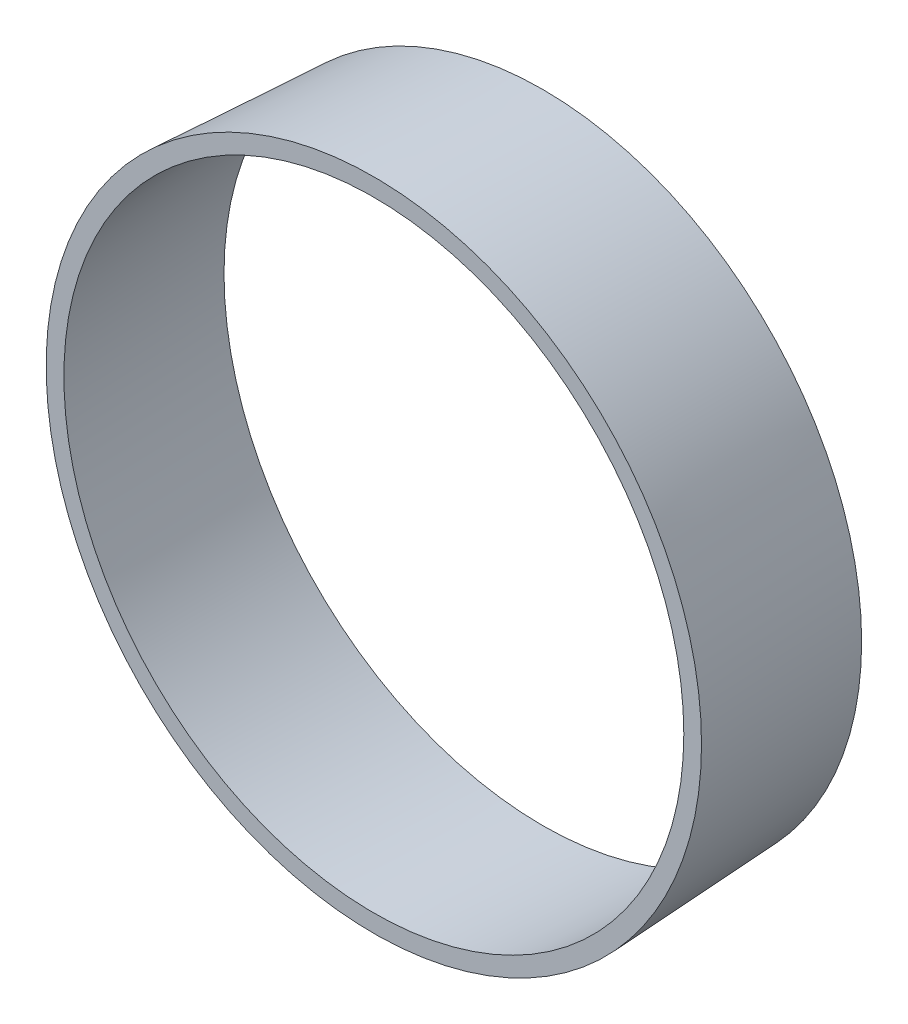
SolidWorks part; units mm, degrees
ref_plane "Front Plane" through (0, 0, 0) normal (0, 0, 1) x (1, 0, 0)
ref_plane "Top Plane" through (0, 0, 0) normal (0, 1, 0) x (1, 0, 0)
ref_plane "Right Plane" through (0, 0, 0) normal (1, 0, 0) x (0, 0, -1)
sketch "Sketch2" plane through (0, 0, 0) normal (0, 0, 1) x (1, 0, 0)
  circle A0 centre (0, 0) radius 17.5
  dimension "D1" = 35
extrude "Extrude-Thin1" add sketch "Sketch2" against normal blind 15 draft 3 thin
